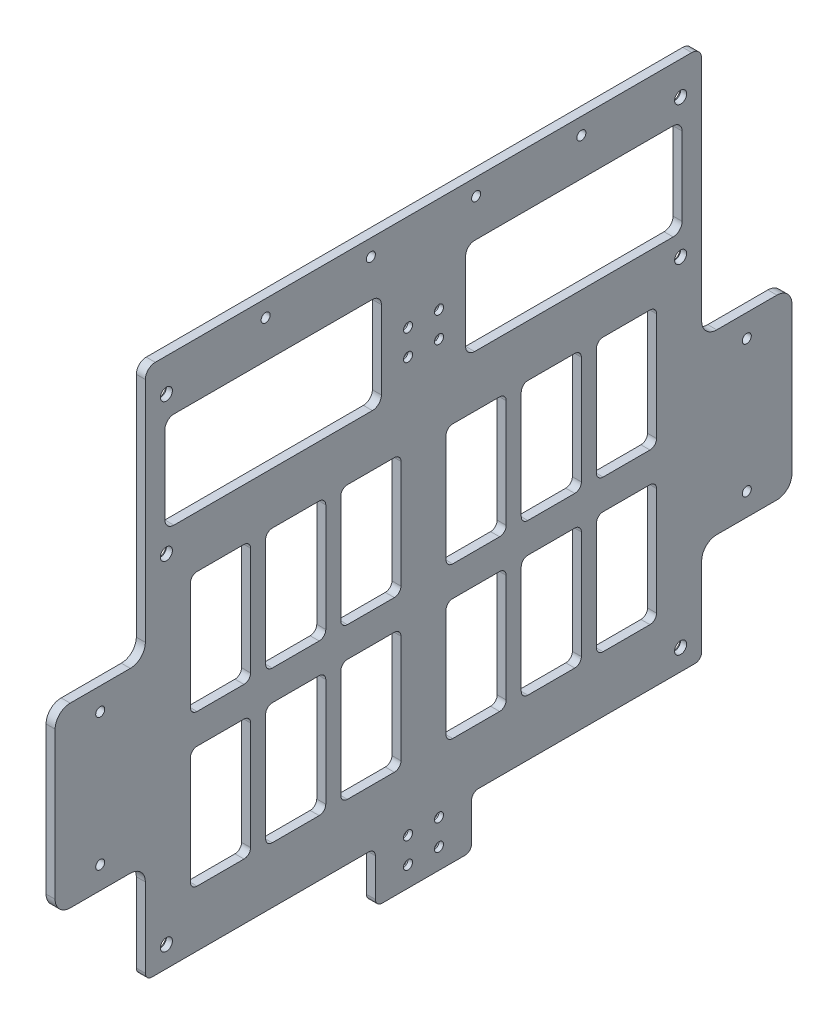
SolidWorks part; units mm, degrees
ref_plane "前视基准面" through (0, 0, 0) normal (0, 0, 1) x (1, 0, 0)
ref_plane "上视基准面" through (0, 0, 0) normal (0, 1, 0) x (1, 0, 0)
ref_plane "右视基准面" through (0, 0, 0) normal (1, 0, 0) x (0, 0, -1)
sketch "草图1" plane through (0, 0, 0) normal (1, 0, 0) x (0, 0, -1)
  line L0 (0, 0) -> (0, 209.0617) construction
  line L1 (13.8, 0) -> (-13.8, 0)
  line L2 (-16, 2.2) -> (-16, 14.79)
  line L3 (-18.2, 16.99) -> (-90.3, 16.99)
  line L4 (-92.5, 19.19) -> (-92.5, 45.49)
  line L5 (-97.5, 50.49) -> (-117.5, 50.49)
  line L6 (-122.5, 55.49) -> (-122.5, 104.49)
  line L7 (-117.5, 109.49) -> (-97.5, 109.49)
  line L8 (-92.5, 114.49) -> (-92.5, 190.19)
  line L9 (-89.2, 193.49) -> (89.2, 193.49)
  line L10 (92.5, 114.49) -> (92.5, 190.19)
  line L11 (117.5, 109.49) -> (97.5, 109.49)
  line L12 (122.5, 55.49) -> (122.5, 104.49)
  line L13 (97.5, 50.49) -> (117.5, 50.49)
  line L14 (92.5, 19.19) -> (92.5, 45.49)
  line L15 (18.2, 16.99) -> (90.3, 16.99)
  line L16 (16, 2.2) -> (16, 14.79)
  arc A0 (-97.5, 109.49) -> (-92.5, 114.49) centre (-97.5, 114.49) ccw
  arc A1 (-92.5, 45.49) -> (-97.5, 50.49) centre (-97.5, 45.49) ccw
  arc A2 (-117.5, 50.49) -> (-122.5, 55.49) centre (-117.5, 55.49) cw
  arc A3 (-122.5, 104.49) -> (-117.5, 109.49) centre (-117.5, 104.49) cw
  arc A4 (92.5, 19.19) -> (90.3, 16.99) centre (90.3, 19.19) cw
  arc A5 (18.2, 16.99) -> (16, 14.79) centre (18.2, 14.79) ccw
  arc A6 (16, 2.2) -> (13.8, 0) centre (13.8, 2.2) cw
  arc A7 (-13.8, 0) -> (-16, 2.2) centre (-13.8, 2.2) cw
  arc A8 (-16, 14.79) -> (-18.2, 16.99) centre (-18.2, 14.79) ccw
  arc A9 (-90.3, 16.99) -> (-92.5, 19.19) centre (-90.3, 19.19) cw
  arc A10 (92.5, 114.49) -> (97.5, 109.49) centre (97.5, 114.49) ccw
  arc A11 (117.5, 109.49) -> (122.5, 104.49) centre (117.5, 104.49) cw
  arc A12 (122.5, 55.49) -> (117.5, 50.49) centre (117.5, 55.49) cw
  arc A13 (97.5, 50.49) -> (92.5, 45.49) centre (97.5, 45.49) ccw
  arc A14 (-92.5, 190.19) -> (-89.2, 193.49) centre (-89.2, 190.19) cw
  arc A15 (92.5, 190.19) -> (89.2, 193.49) centre (89.2, 190.19) ccw
  point P15 (0, 193.49)
  point P24 (-92.5, 109.49)
  point P27 (-92.5, 50.49)
  point P30 (-122.5, 50.49)
  point P33 (-122.5, 109.49)
  point P36 (92.5, 16.99)
  point P39 (16, 16.99)
  point P42 (16, 0)
  point P45 (-16, 0)
  point P48 (-16, 16.99)
  point P51 (-92.5, 16.99)
  point P54 (92.5, 109.49)
  point P57 (122.5, 109.49)
  point P60 (122.5, 50.49)
  point P63 (92.5, 50.49)
  point P66 (-92.5, 193.49)
  point P69 (92.5, 193.49)
  dimension "D9" = 5
  dimension "D10" = 2.2
  dimension "D11" = 5
  dimension "D12" = 3.3
  dimension "D1" = 193.49
  dimension "D2" = 176.5
  dimension "D3" = 185
  dimension "D4" = 59
  dimension "D5" = 76.5
  dimension "D6" = 32
  dimension "D7" = 245
  dimension "D8" = 84
extrude "凸台-拉伸1" add sketch "草图1" along normal blind 3
sketch "草图2" plane through (3, 0, 0) normal (1, 0, 0) x (0, 0, -1)
  line L0 (0, 0) -> (0, 15) construction
  line L2 (-17, 143.49) -> (-83, 143.49)
  line L3 (-14, 146.49) -> (-14, 172.49)
  line L4 (-17, 175.49) -> (-83, 175.49)
  line L5 (-86, 146.49) -> (-86, 172.49)
  line L6 (-14, 143.49) -> (-86, 175.49) construction
  line L7 (-14, 175.49) -> (-86, 143.49) construction
  line L8 (17, 143.49) -> (83, 143.49)
  line L9 (14, 146.49) -> (14, 172.49)
  line L10 (17, 175.49) -> (83, 175.49)
  line L11 (86, 146.49) -> (86, 172.49)
  line L13 (89.2, 193.49) -> (-89.2, 193.49) construction
  line L14 (-34.7, 126.29) -> (-50.3, 126.29)
  line L15 (-9.7, 126.29) -> (-25.3, 126.29)
  line L16 (-7.5, 124.09) -> (-7.5, 88.19)
  line L17 (-9.7, 85.99) -> (-25.3, 85.99)
  line L18 (-27.5, 124.09) -> (-27.5, 88.19)
  line L19 (-32.5, 124.09) -> (-32.5, 88.19)
  line L20 (-34.7, 85.99) -> (-50.3, 85.99)
  line L21 (-52.5, 124.09) -> (-52.5, 88.19)
  line L22 (-59.7, 126.29) -> (-75.3, 126.29)
  line L23 (-57.5, 124.09) -> (-57.5, 88.19)
  line L24 (-59.7, 85.99) -> (-75.3, 85.99)
  line L25 (-77.5, 124.09) -> (-77.5, 88.19)
  line L26 (-9.7, 126.29) -> (-34.7, 126.29) construction
  line L27 (-34.7, 75.99) -> (-50.3, 75.99)
  line L28 (-9.7, 75.99) -> (-25.3, 75.99)
  line L29 (-7.5, 73.79) -> (-7.5, 37.89)
  line L30 (-9.7, 35.69) -> (-25.3, 35.69)
  line L31 (-27.5, 73.79) -> (-27.5, 37.89)
  line L32 (-32.5, 73.79) -> (-32.5, 37.89)
  line L33 (-34.7, 35.69) -> (-50.3, 35.69)
  line L34 (-52.5, 73.79) -> (-52.5, 37.89)
  line L35 (-59.7, 75.99) -> (-75.3, 75.99)
  line L36 (-57.5, 73.79) -> (-57.5, 37.89)
  line L37 (-59.7, 35.69) -> (-75.3, 35.69)
  line L38 (-77.5, 73.79) -> (-77.5, 37.89)
  line L39 (-9.7, 75.99) -> (-34.7, 75.99) construction
  line L40 (-34.7, 126.29) -> (-34.7, 75.99) construction
  line L41 (0, 0) -> (0, 216.7659) construction
  line L42 (34.7, 126.29) -> (34.7, 75.99) construction
  line L43 (9.7, 75.99) -> (34.7, 75.99) construction
  line L44 (9.7, 126.29) -> (34.7, 126.29) construction
  line L45 (77.5, 73.79) -> (77.5, 37.89)
  line L46 (59.7, 35.69) -> (75.3, 35.69)
  line L47 (57.5, 73.79) -> (57.5, 37.89)
  line L48 (59.7, 75.99) -> (75.3, 75.99)
  line L49 (52.5, 73.79) -> (52.5, 37.89)
  line L50 (34.7, 35.69) -> (50.3, 35.69)
  line L51 (32.5, 73.79) -> (32.5, 37.89)
  line L52 (27.5, 73.79) -> (27.5, 37.89)
  line L53 (9.7, 35.69) -> (25.3, 35.69)
  line L54 (7.5, 73.79) -> (7.5, 37.89)
  line L55 (9.7, 75.99) -> (25.3, 75.99)
  line L56 (34.7, 75.99) -> (50.3, 75.99)
  line L57 (77.5, 124.09) -> (77.5, 88.19)
  line L58 (59.7, 85.99) -> (75.3, 85.99)
  line L59 (57.5, 124.09) -> (57.5, 88.19)
  line L60 (59.7, 126.29) -> (75.3, 126.29)
  line L61 (52.5, 124.09) -> (52.5, 88.19)
  line L62 (34.7, 85.99) -> (50.3, 85.99)
  line L63 (32.5, 124.09) -> (32.5, 88.19)
  line L64 (27.5, 124.09) -> (27.5, 88.19)
  line L65 (9.7, 85.99) -> (25.3, 85.99)
  line L66 (7.5, 124.09) -> (7.5, 88.19)
  line L67 (9.7, 126.29) -> (25.3, 126.29)
  line L68 (34.7, 126.29) -> (50.3, 126.29)
  line L69 (-97.5, 109.49) -> (-117.5, 109.49) construction
  line L70 (-122.5, 104.49) -> (-122.5, 55.49) construction
  line L71 (-117.5, 50.49) -> (-97.5, 50.49) construction
  line L73 (-92.5, 45.49) -> (-92.5, 19.19) construction
  line L76 (-13.8, 0) -> (13.8, 0) construction
  line L77 (5.15, 15.26) -> (5.15, 161.5) construction
  line L78 (-90.3, 16.99) -> (-18.2, 16.99) construction
  line L79 (-92.5, 45.49) -> (-92.5, 19.19) construction
  line L80 (89.2, 193.49) -> (-89.2, 193.49) construction
  arc A0 (-83, 143.49) -> (-86, 146.49) centre (-83, 146.49) cw
  arc A1 (-17, 143.49) -> (-14, 146.49) centre (-17, 146.49) ccw
  arc A2 (-14, 172.49) -> (-17, 175.49) centre (-17, 172.49) ccw
  arc A3 (-83, 175.49) -> (-86, 172.49) centre (-83, 172.49) ccw
  arc A4 (17, 143.49) -> (14, 146.49) centre (17, 146.49) cw
  arc A5 (83, 143.49) -> (86, 146.49) centre (83, 146.49) ccw
  arc A6 (83, 175.49) -> (86, 172.49) centre (83, 172.49) cw
  arc A7 (14, 172.49) -> (17, 175.49) centre (17, 172.49) cw
  arc A8 (-9.7, 126.29) -> (-7.5, 124.09) centre (-9.7, 124.09) cw
  arc A9 (-7.5, 88.19) -> (-9.7, 85.99) centre (-9.7, 88.19) cw
  arc A10 (-25.3, 85.99) -> (-27.5, 88.19) centre (-25.3, 88.19) cw
  arc A11 (-25.3, 126.29) -> (-27.5, 124.09) centre (-25.3, 124.09) ccw
  arc A12 (-34.7, 126.29) -> (-32.5, 124.09) centre (-34.7, 124.09) cw
  arc A13 (-32.5, 88.19) -> (-34.7, 85.99) centre (-34.7, 88.19) cw
  arc A14 (-50.3, 85.99) -> (-52.5, 88.19) centre (-50.3, 88.19) cw
  arc A15 (-50.3, 126.29) -> (-52.5, 124.09) centre (-50.3, 124.09) ccw
  arc A16 (-59.7, 126.29) -> (-57.5, 124.09) centre (-59.7, 124.09) cw
  arc A17 (-57.5, 88.19) -> (-59.7, 85.99) centre (-59.7, 88.19) cw
  arc A18 (-75.3, 85.99) -> (-77.5, 88.19) centre (-75.3, 88.19) cw
  arc A19 (-75.3, 126.29) -> (-77.5, 124.09) centre (-75.3, 124.09) ccw
  arc A20 (-9.7, 75.99) -> (-7.5, 73.79) centre (-9.7, 73.79) cw
  arc A21 (-7.5, 37.89) -> (-9.7, 35.69) centre (-9.7, 37.89) cw
  arc A22 (-25.3, 35.69) -> (-27.5, 37.89) centre (-25.3, 37.89) cw
  arc A23 (-25.3, 75.99) -> (-27.5, 73.79) centre (-25.3, 73.79) ccw
  arc A24 (-34.7, 75.99) -> (-32.5, 73.79) centre (-34.7, 73.79) cw
  arc A25 (-32.5, 37.89) -> (-34.7, 35.69) centre (-34.7, 37.89) cw
  arc A26 (-50.3, 35.69) -> (-52.5, 37.89) centre (-50.3, 37.89) cw
  arc A27 (-50.3, 75.99) -> (-52.5, 73.79) centre (-50.3, 73.79) ccw
  arc A28 (-59.7, 75.99) -> (-57.5, 73.79) centre (-59.7, 73.79) cw
  arc A29 (-57.5, 37.89) -> (-59.7, 35.69) centre (-59.7, 37.89) cw
  arc A30 (-75.3, 35.69) -> (-77.5, 37.89) centre (-75.3, 37.89) cw
  arc A31 (-75.3, 75.99) -> (-77.5, 73.79) centre (-75.3, 73.79) ccw
  arc A32 (75.3, 75.99) -> (77.5, 73.79) centre (75.3, 73.79) cw
  arc A33 (75.3, 35.69) -> (77.5, 37.89) centre (75.3, 37.89) ccw
  arc A34 (57.5, 37.89) -> (59.7, 35.69) centre (59.7, 37.89) ccw
  arc A35 (59.7, 75.99) -> (57.5, 73.79) centre (59.7, 73.79) ccw
  arc A36 (50.3, 75.99) -> (52.5, 73.79) centre (50.3, 73.79) cw
  arc A37 (50.3, 35.69) -> (52.5, 37.89) centre (50.3, 37.89) ccw
  arc A38 (32.5, 37.89) -> (34.7, 35.69) centre (34.7, 37.89) ccw
  arc A39 (34.7, 75.99) -> (32.5, 73.79) centre (34.7, 73.79) ccw
  arc A40 (25.3, 75.99) -> (27.5, 73.79) centre (25.3, 73.79) cw
  arc A41 (25.3, 35.69) -> (27.5, 37.89) centre (25.3, 37.89) ccw
  arc A42 (7.5, 37.89) -> (9.7, 35.69) centre (9.7, 37.89) ccw
  arc A43 (9.7, 75.99) -> (7.5, 73.79) centre (9.7, 73.79) ccw
  arc A44 (75.3, 126.29) -> (77.5, 124.09) centre (75.3, 124.09) cw
  arc A45 (75.3, 85.99) -> (77.5, 88.19) centre (75.3, 88.19) ccw
  arc A46 (57.5, 88.19) -> (59.7, 85.99) centre (59.7, 88.19) ccw
  arc A47 (59.7, 126.29) -> (57.5, 124.09) centre (59.7, 124.09) ccw
  arc A48 (50.3, 126.29) -> (52.5, 124.09) centre (50.3, 124.09) cw
  arc A49 (50.3, 85.99) -> (52.5, 88.19) centre (50.3, 88.19) ccw
  arc A50 (32.5, 88.19) -> (34.7, 85.99) centre (34.7, 88.19) ccw
  arc A51 (34.7, 126.29) -> (32.5, 124.09) centre (34.7, 124.09) ccw
  arc A52 (25.3, 126.29) -> (27.5, 124.09) centre (25.3, 124.09) cw
  arc A53 (25.3, 85.99) -> (27.5, 88.19) centre (25.3, 88.19) ccw
  arc A54 (7.5, 88.19) -> (9.7, 85.99) centre (9.7, 88.19) ccw
  arc A55 (9.7, 126.29) -> (7.5, 124.09) centre (9.7, 124.09) ccw
  circle A56 centre (-107.5, 101.99) radius 1.5
  circle A57 centre (-107.5, 57.99) radius 1.5
  circle A58 centre (-52.5, 187.99) radius 1.5
  circle A59 centre (-17.5, 187.99) radius 1.5
  circle A60 centre (17.5, 187.99) radius 1.5
  circle A61 centre (52.5, 187.99) radius 1.5
  circle A62 centre (107.5, 57.99) radius 1.5
  circle A63 centre (107.5, 101.99) radius 1.5
  circle A64 centre (5.15, 15.26) radius 1.5
  circle A65 centre (5.15, 6.76) radius 1.5
  circle A66 centre (-5.15, 6.76) radius 1.5
  circle A67 centre (-5.15, 15.26) radius 1.5
  circle A68 centre (5.15, 161.5) radius 1.5
  circle A69 centre (5.15, 153) radius 1.5
  circle A70 centre (-5.15, 153) radius 1.5
  circle A71 centre (-5.15, 161.5) radius 1.5
  circle A72 centre (-85.5, 23.99) radius 2
  circle A73 centre (-85.5, 182.49) radius 2
  circle A74 centre (-85.5, 136.49) radius 2
  circle A75 centre (85.5, 23.99) radius 2
  circle A76 centre (85.5, 136.49) radius 2
  circle A77 centre (85.5, 182.49) radius 2
  point P3 (-50, 159.49)
  point P40 (-7.5, 126.29)
  point P43 (-7.5, 85.99)
  point P46 (-27.5, 85.99)
  point P188 (27.5, 85.99)
  point P189 (7.5, 85.99)
  point P190 (7.5, 126.29)
  dimension "D5" = 3
  dimension "D9" = 2.2
  dimension "D15" = 3
  dimension "D16" = 3
  dimension "D18" = 15
  dimension "D19" = 7.5
  dimension "D20" = 3
  dimension "D21" = 3
  dimension "D24" = 35
  dimension "D25" = 3
  dimension "D26" = 3
  dimension "D32" = 4
  dimension "D33" = 7
  dimension "D35" = 7
  dimension "D1" = 28
  dimension "D2" = 18
  dimension "D3" = 32
  dimension "D4" = 72
  dimension "D6" = 17.2
  dimension "D7" = 40.3
  dimension "D8" = 20
  dimension "D10" = 15
  dimension "D11" = 3
  dimension "D12" = 25
  dimension "D14" = 50.3
  dimension "D17" = 7.5
  dimension "D22" = 5.5
  dimension "D23" = 40
  dimension "D27" = 8.5
  dimension "D28" = 10.3
  dimension "D29" = 6.76
  dimension "D31" = 146.24
  dimension "D34" = 7
  dimension "D36" = 7
  dimension "D13" = 2
  dimension "D30" = 2
extrude "切除-拉伸1" cut sketch "草图2" against normal through all
chamfer "倒角2" distance 1.5 angle 45 8 edges at (0, 153, -6.65) (0, 153, 6.65) (0, 161.5, 6.65) (0, 161.5, -6.65) (0, 6.76, -6.65) (0, 6.76, 6.65) (0, 15.26, 6.65) (0, 15.26, -6.65)
chamfer "倒角3" distance 1 angle 45 6 edges at (0, 182.49, -83.5) (0, 182.49, 83.5) (0, 136.49, 83.5) (0, 23.99, 83.5) (0, 136.49, -83.5) (0, 23.99, -83.5)
